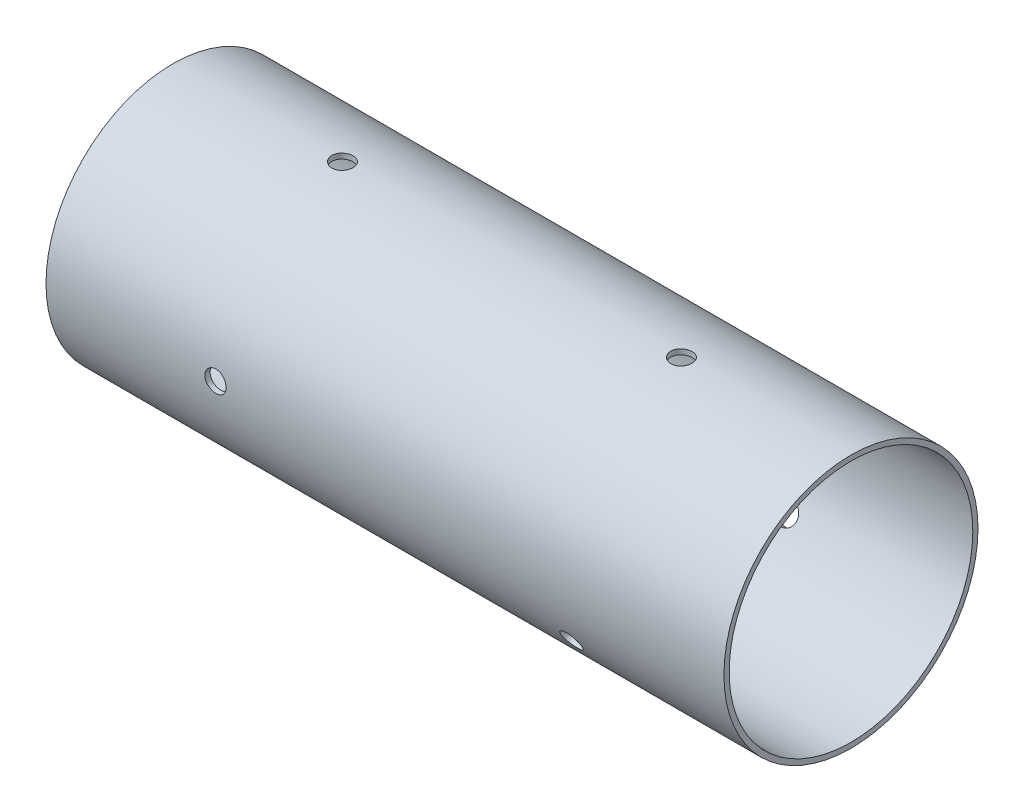
SolidWorks part; units mm, degrees
ref_plane "Front Plane" through (0, 0, 0) normal (1, 0, 0) x (0, 1, 0)
ref_plane "Top Plane" through (0, 0, 0) normal (0, 0, 1) x (0, 1, 0)
ref_plane "Right Plane" through (0, 0, 0) normal (0, 1, 0) x (-1, 0, 0)
sketch "Sketch1" plane through (0, 0, 0) normal (1, 0, 0) x (0, 1, 0)
  circle A0 centre (0, 0) radius 38.0746
  circle A1 centre (0, 0) radius 36.5125
  dimension "D1" = 76.1492
  dimension "D2" = 73.025
extrude "Boss-Extrude1" add sketch "Sketch1" along normal blind 203.2
sketch "Sketch2" plane through (0, 0, 0) normal (0, 1, 0) x (-1, 0, 0)
  circle A0 centre (-50.8, 0) radius 3.175
  point P2 (0, 0)
  dimension "D2" = 6.35
  dimension "D1" = 50.8
extrude "Cut-Extrude1" cut sketch "Sketch2" along normal through all
pattern_circular "CirPattern1" count 4 over 360 about axis through (203.2, 0, 0) along (-1, 0, 0) of "Cut-Extrude1"
sketch "Sketch3" plane through (0, 0, 0) normal (0, 1, 0) x (-1, 0, 0)
  line L0 (-203.2, 38.0746) -> (-203.2, -38.0746) construction
  circle A0 centre (-152.4, 0) radius 3.175
  point P4 (0, 0)
  dimension "D1" = 6.35
  dimension "D2" = 50.8
extrude "Cut-Extrude2" cut sketch "Sketch3" along normal through all
pattern_circular "CirPattern2" count 3 over 360 about axis through (203.2, 0, 0) along (-1, 0, 0) of "Cut-Extrude2"
